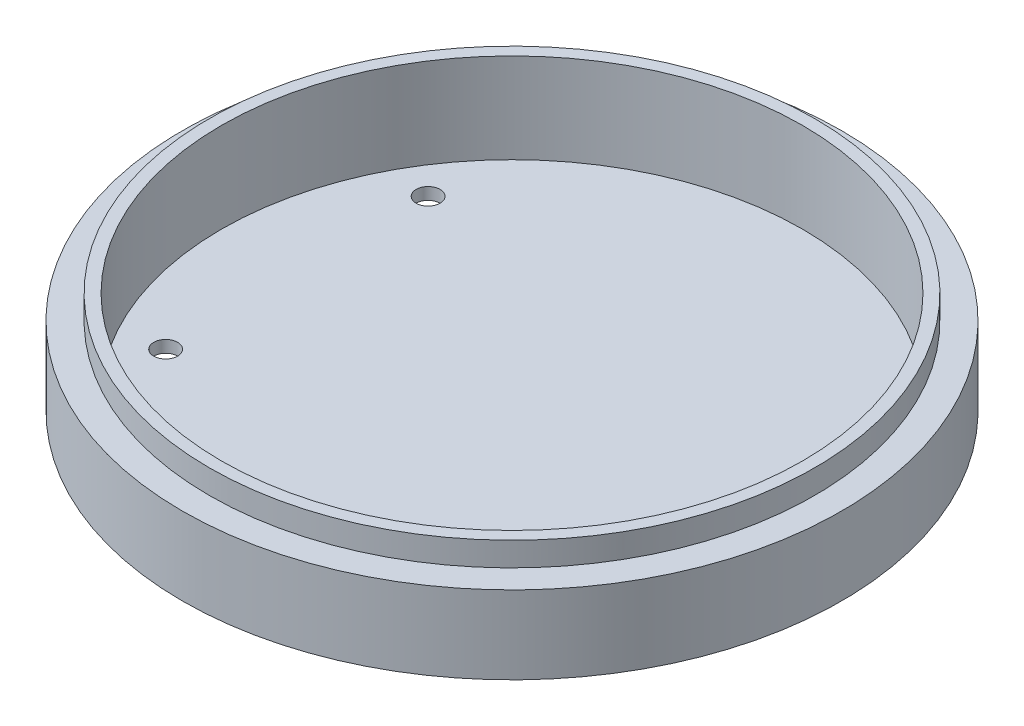
SolidWorks part; units mm, degrees
ref_plane "Front Plane" through (0, 0, 0) normal (0, 0, 1) x (1, 0, 0)
ref_plane "Top Plane" through (0, 0, 0) normal (0, 1, 0) x (1, 0, 0)
ref_plane "Right Plane" through (0, 0, 0) normal (1, 0, 0) x (0, 0, -1)
sketch "Sketch2" plane through (0, 0, 0) normal (0, 1, 0) x (1, 0, 0)
  circle A0 centre (0, 0) radius 55
  circle A1 centre (0, 0) radius 52.5
  dimension "D1" = 110
  dimension "D2" = 105
extrude "Boss-Extrude2" add sketch "Sketch2" along normal blind 13 contours A0
sketch "Sketch3" plane through (0, 0, 0) normal (0, -1, 0) x (1, 0, 0)
  circle A0 centre (0, 0) radius 52.5
  dimension "D1" = 105
sketch "Sketch7" plane through (0, 13, 0) normal (0, 1, 0) x (1, 0, 0)
  circle A0 centre (0, 0) radius 50.5
  dimension "D1" = 101
extrude "Boss-Extrude3" add sketch "Sketch7" along normal blind 4
sketch "Sketch8" plane through (0, 17, 0) normal (0, 1, 0) x (1, 0, 0)
  circle A0 centre (0, 0) radius 48.5
  dimension "D1" = 97
extrude "Cut-Extrude3" cut sketch "Sketch8" against normal blind 15
sketch "Sketch9" plane through (0, 2, 0) normal (0, 1, 0) x (1, 0, 0)
  line L1 (-38, -24) -> (38, -24)
  line L2 (-38, -24) -> (-38, 24)
  line L3 (-38, 24) -> (38, 24)
  line L4 (38, -24) -> (38, 24)
  circle A0 centre (-35.8, -22) radius 2
  circle A1 centre (36, -22) radius 2
  circle A2 centre (36, 22) radius 2
  circle A3 centre (-36, 22) radius 2
  point P13 (0, 0)
  dimension "D5" = 4
  dimension "D6" = 4
  dimension "D7" = 4
  dimension "D8" = 4
  dimension "D1" = 76
  dimension "D2" = 38
  dimension "D3" = 48
  dimension "D4" = 24
  dimension "D9" = 2.2
  dimension "D10" = 2
  dimension "D11" = 2
  dimension "D12" = 2
  dimension "D13" = 2
  dimension "D14" = 2
extrude "Cut-Extrude4" cut sketch "Sketch9" against normal blind 15 contours A1 | A3 | A0 | A2
